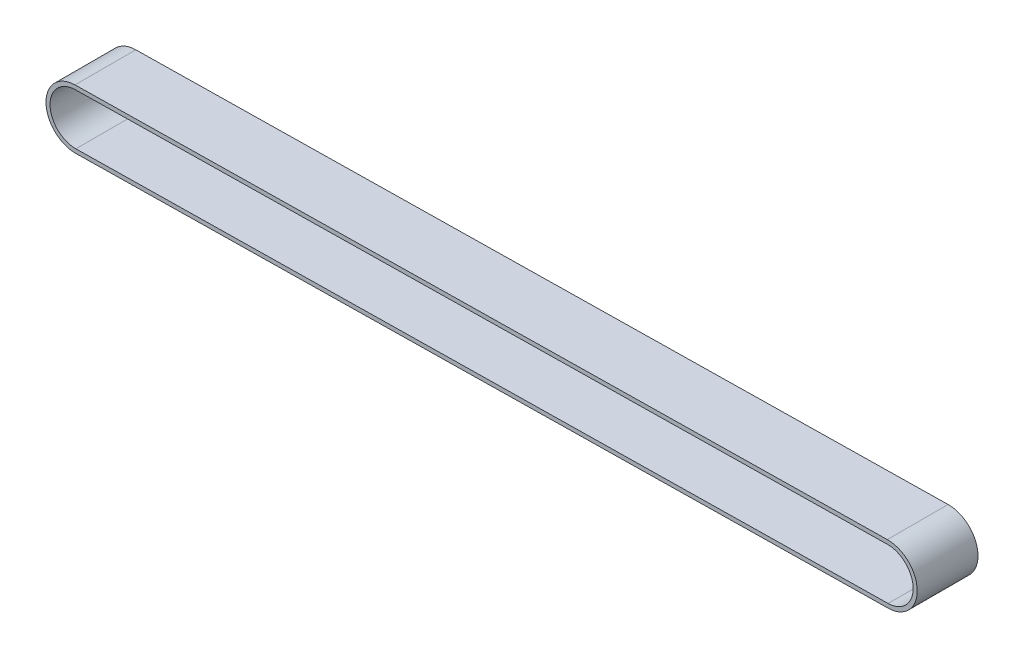
SolidWorks part; units mm, degrees
ref_plane "Front Plane" through (0, 0, 0) normal (0, 0, 1) x (1, 0, 0)
ref_plane "Top Plane" through (0, 0, 0) normal (0, 1, 0) x (1, 0, 0)
ref_plane "Right Plane" through (0, 0, 0) normal (1, 0, 0) x (0, 0, -1)
sketch "Sketch2" plane through (0, 0, 0) normal (0, 0, 1) x (1, 0, 0)
  line L0 (0, 0) -> (1, 0) construction
  line L1 (0, 0) -> (0, 1) construction
  line L2 (-0.1031, 6.7792) -> (200.3583, 9.8292)
  line L3 (200.5646, -3.7292) -> (0.1031, -6.7792)
  arc A0 (0.1031, -6.7792) -> (-0.1031, 6.7792) centre (0, 0) cw
  arc A1 (200.3583, 9.8292) -> (200.5646, -3.7292) centre (200.4614, 3.05) cw
extrude "Extrude-Thin1" add sketch "Sketch2" along normal mid plane 15 thin thin type mid plane wall 1
